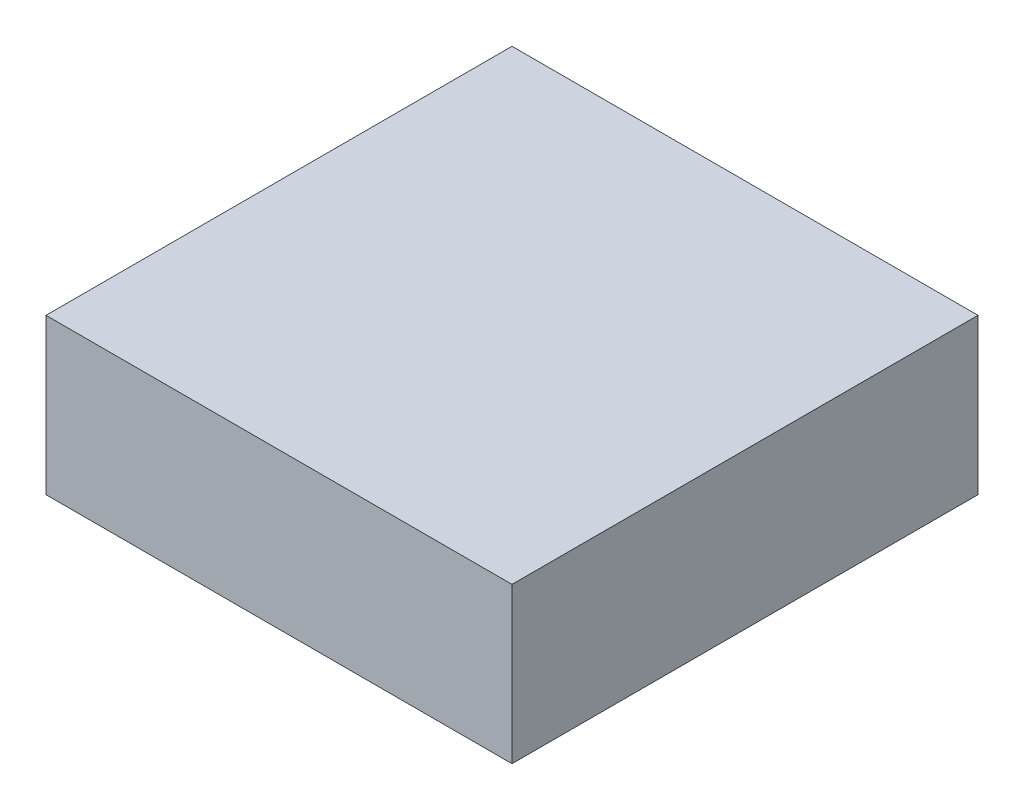
SolidWorks part; units mm, degrees
ref_plane "前视基准面" through (0, 0, 0) normal (0, 0, 1) x (1, 0, 0)
ref_plane "上视基准面" through (0, 0, 0) normal (0, 1, 0) x (1, 0, 0)
ref_plane "右视基准面" through (0, 0, 0) normal (1, 0, 0) x (0, 0, -1)
sketch "草图1" plane through (0, 0, 0) normal (0, 1, 0) x (1, 0, 0)
  line L1 (-15, 15) -> (15, 15)
  line L2 (-15, 15) -> (-15, -15)
  line L3 (-15, -15) -> (15, -15)
  line L4 (15, 15) -> (15, -15)
  line L5 (-15, 15) -> (15, -15) construction
  line L6 (-15, -15) -> (15, 15) construction
  point P0 (0, 0)
  dimension "D1" = 30
  dimension "D2" = 30
extrude "凸台-拉伸1" add sketch "草图1" along normal blind 10
